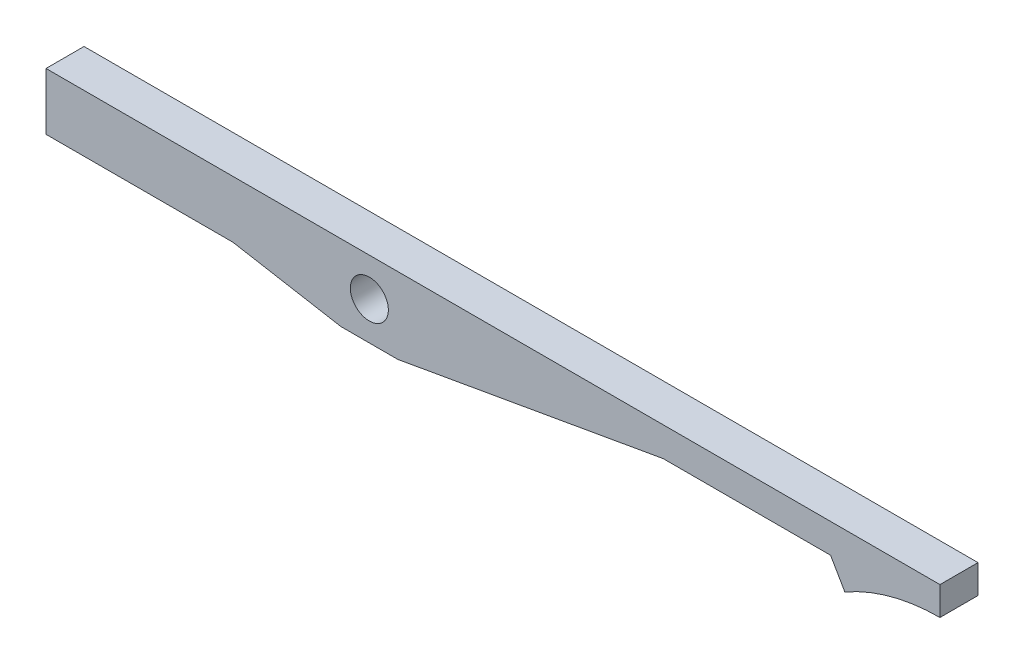
SolidWorks part; units mm, degrees
ref_plane "Přední rovina" through (0, 0, 0) normal (0, 0, 1) x (1, 0, 0)
ref_plane "Horní rovina" through (0, 0, 0) normal (0, 1, 0) x (1, 0, 0)
ref_plane "Pravá rovina" through (0, 0, 0) normal (1, 0, 0) x (0, 0, -1)
sketch "Skica1" plane through (0, 0, 0) normal (0, 0, 1) x (1, 0, 0)
  line L0 (0, 0) -> (0, -1.5)
  line L1 (-5, -2.8397) -> (-5.75, -1.5407)
  line L2 (0, 0) -> (-47, 0)
  line L3 (-5.75, -1.5407) -> (-14.5527, -1.5407)
  line L4 (-47, -3) -> (-37.1713, -3)
  line L7 (-47, 0) -> (-47, -3)
  line L8 (-37.1713, -3) -> (-31.5, -4)
  line L9 (-31.5, -4) -> (-28.5, -4)
  line L10 (-30, 0) -> (-30, -4) construction
  line L11 (-14.5527, -1.5407) -> (-28.5, -4)
  arc A0 (0, -1.5) -> (-5, -2.8397) centre (0, -11.5) ccw
  circle A2 centre (-30, -2) radius 1
  point P20 (-50.9898, 0.5137)
  dimension "D3" = 10
  dimension "D4" = 2
  dimension "D8" = 30
  dimension "D5" = 2
  dimension "D1" = 1.5
  dimension "D2" = 30
  dimension "D6" = 47
  dimension "D7" = 3
  dimension "D9" = 10
  dimension "D10" = 3
extrude "Přidat vysunutím1" add sketch "Skica1" along normal blind 2
